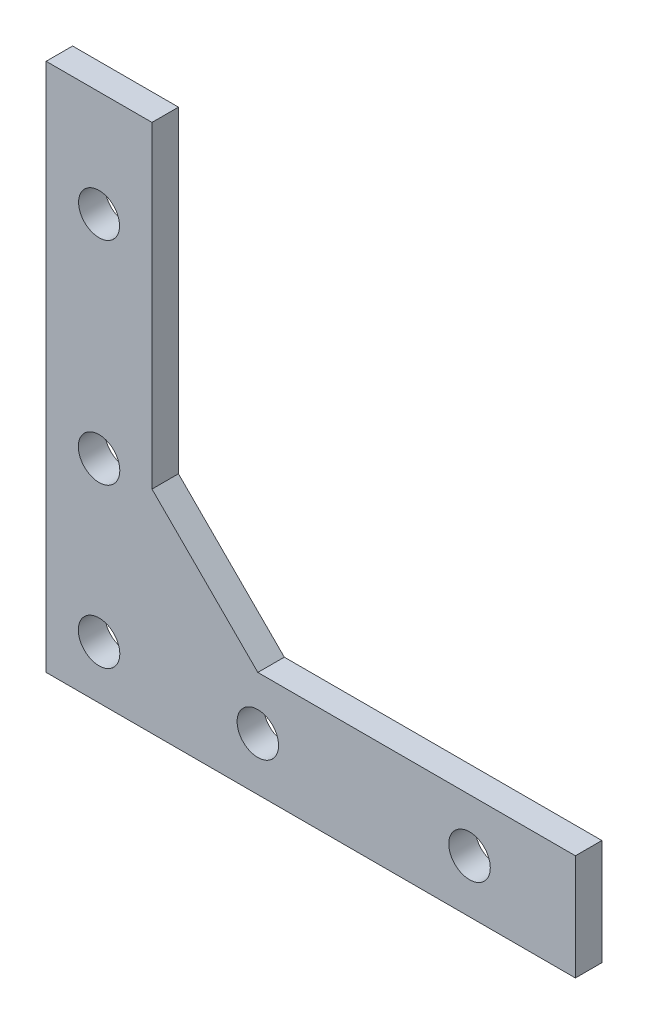
SolidWorks part; units mm, degrees
material "6061 Alloy"
ref_plane "Front Plane" through (0, 0, 0) normal (0, 0, 1) x (1, 0, 0)
ref_plane "Top Plane" through (0, 0, 0) normal (0, 1, 0) x (1, 0, 0)
ref_plane "Right Plane" through (0, 0, 0) normal (1, 0, 0) x (0, 0, -1)
sketch "Sketch1" plane through (0, 0, 0) normal (0, 0, 1) x (1, 0, 0)
  line L0 (-253.5966, 0) -> (-266.7, 0)
  line L1 (-266.7, 0) -> (-266.7, 63.5)
  line L2 (-266.7, 63.5) -> (-254, 63.5)
  line L3 (-254, -16.7024) -> (-254, 609.6) construction
  line L4 (-253.5966, 0) -> (-203.2, 0)
  line L6 (-203.2, 0) -> (-203.2, 12.7)
  line L7 (-254, 12.7) -> (254, 12.7) construction
  line L8 (-203.2, 12.7) -> (-241.3, 12.7)
  line L9 (-241.3, 12.7) -> (-254, 25.4)
  line L10 (-254, 25.4) -> (-254, 63.5)
  dimension "D1" = 63.5
  dimension "D2" = 12.7
  dimension "D3" = 38.1
  dimension "D4" = 12.7
  dimension "D5" = 38.1
  dimension "D6" = 63.5
extrude "Boss-Extrude1" add sketch "Sketch1" along normal blind 3.175
sketch "Sketch2" plane through (0, 0, 3.175) normal (0, 0, 1) x (1, 0, 0)
  line L0 (-260.35, 63.5) -> (-260.35, 50.8) construction
  line L1 (-254, 63.5) -> (-266.7, 63.5) construction
  line L2 (-260.35, 50.8) -> (-260.35, 25.4) construction
  line L3 (-260.35, 6.35) -> (-241.3, 6.35) construction
  line L4 (-260.35, 25.4) -> (-260.35, 6.35) construction
  line L5 (-241.3, 6.35) -> (-215.9, 6.35) construction
  line L6 (-203.2, 6.35) -> (-215.9, 6.35) construction
  line L7 (-203.2, 0) -> (-203.2, 12.7) construction
  dimension "D1" = 19.05
  dimension "D2" = 19.05
  dimension "D3" = 25.4
  dimension "D4" = 25.4
hole_wizard "#10 Clearance Hole1" positions "Sketch3" profile "Sketch4" hole size "#10" standard "ANSI Inch" end condition through all
sketch "Sketch3" plane through (0, 0, 3.175) normal (0, 0, 1) x (1, 0, 0)
  point P0 (-260.35, 6.35)
  point P3 (-260.35, 25.4)
  point P9 (-241.3, 6.35)
  point P12 (-215.9, 6.35)
sketch "Sketch4" plane through (-260.35, 6.35, 3.175) normal (1, 0, 0) x (0, -1, 0)
  line L0 (0, 0) -> (0, 3.175)
  line L1 (0, 3.175) -> (2.4892, 3.175)
  line L2 (2.4892, 3.175) -> (2.4892, 0)
  line L5 (2.4892, 0) -> (0, 0)
  line L11 (0, -6.35) -> (0, 107.95) construction
  dimension "Thru Hole Dia." = 4.9784
  dimension "Thru Hole Depth" = 3.175
hole_wizard "#10 (0.1935) Diameter Hole1" positions "Sketch7" profile "Sketch8" hole size "#10" standard "ANSI Inch" end condition through all
sketch "Sketch7" plane through (0, 0, 3.175) normal (0, 0, 1) x (1, 0, 0)
  point P0 (-260.35, 50.8)
sketch "Sketch8" plane through (-260.35, 50.8, 3.175) normal (1, 0, 0) x (0, -1, 0)
  line L0 (0, 0) -> (0, 3.175)
  line L1 (0, 3.175) -> (2.4574, 3.175)
  line L2 (2.4574, 3.175) -> (2.4574, 0)
  line L5 (2.4574, 0) -> (0, 0)
  line L11 (0, -6.35) -> (0, 107.95) construction
  dimension "Thru Hole Dia." = 4.9149
  dimension "Thru Hole Depth" = 3.175
